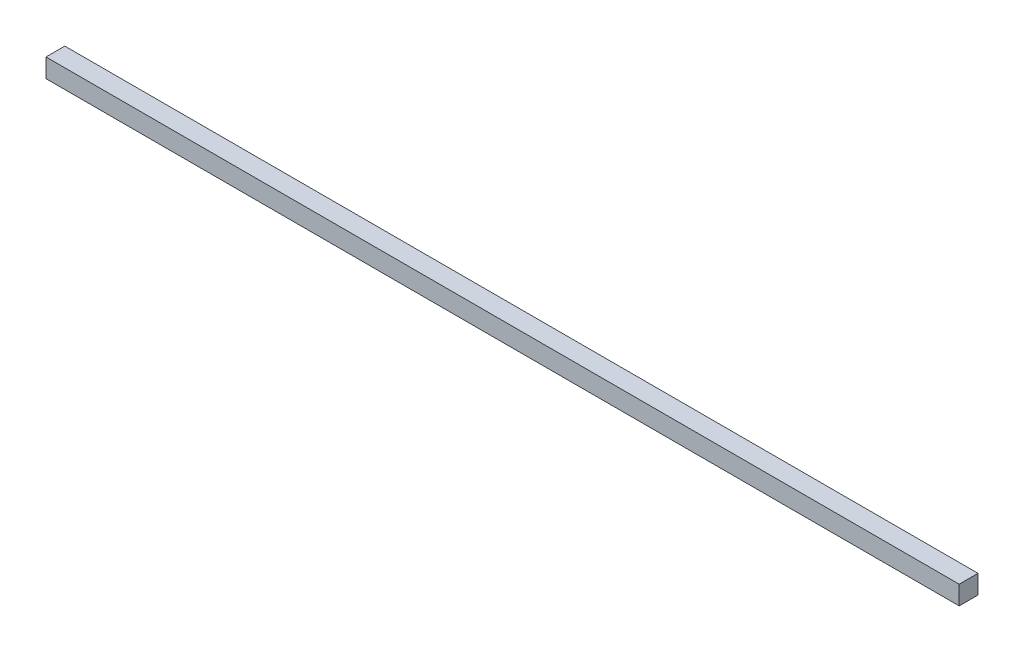
SolidWorks part; units mm, degrees
ref_plane "Front Plane" through (0, 0, 0) normal (0, 0, 1) x (1, 0, 0)
ref_plane "Top Plane" through (0, 0, 0) normal (0, 1, 0) x (1, 0, 0)
ref_plane "Right Plane" through (0, 0, 0) normal (1, 0, 0) x (0, 0, -1)
sketch "Sketch1" plane through (0, 0, 0) normal (1, 0, 0) x (0, 0, -1)
  line L1 (0, 0) -> (6.35, 0)
  line L2 (0, 0) -> (0, 6.35)
  line L3 (0, 6.35) -> (6.35, 6.35)
  line L4 (6.35, 0) -> (6.35, 6.35)
  dimension "D1" = 6.35
extrude "Boss-Extrude1" add sketch "Sketch1" along normal blind 307.975
